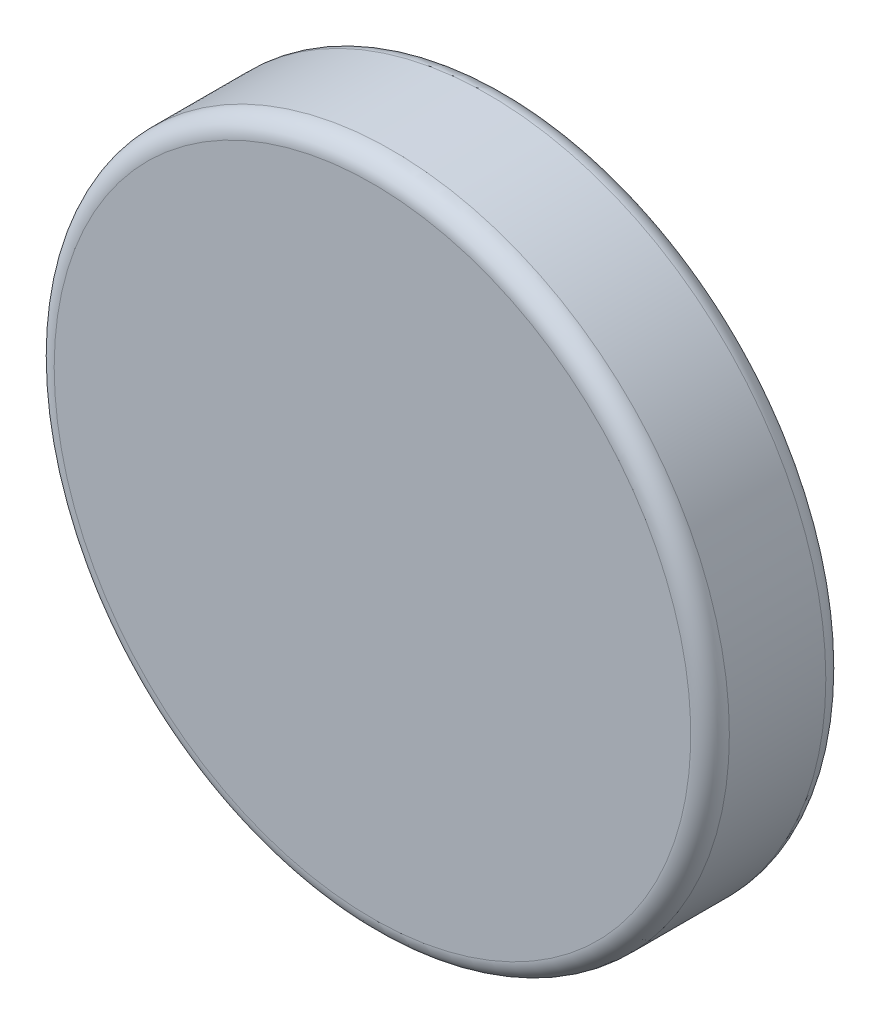
SolidWorks part; units mm, degrees
ref_plane "Front Plane" through (0, 0, 0) normal (0, 0, 1) x (1, 0, 0)
ref_plane "Top Plane" through (0, 0, 0) normal (0, 1, 0) x (1, 0, 0)
ref_plane "Right Plane" through (0, 0, 0) normal (1, 0, 0) x (0, 0, -1)
sketch "Sketch1" plane through (0, 0, 0) normal (0, 0, 1) x (1, 0, 0)
  circle A0 centre (-133.2708, 0) radius 4
  dimension "D1" = 8
extrude "Boss-Extrude1" add sketch "Sketch1" along normal blind 1
sketch "Sketch2" plane through (0, 0, 1) normal (0, 0, 1) x (1, 0, 0)
  arc A0 (-125.3812, 3.7838) -> (-125.3812, -3.7838) centre (-133.2708, 0) cw
  arc A2 (-125.3812, 3.7838) -> (-125.3812, -3.7838) centre (-133.2708, 0) ccw
  arc A3 (-125.3812, 3.7838) -> (-125.3812, -3.7838) centre (-133.2708, 0) ccw
  dimension "D1" = 0.5
extrude "Boss-Extrude2" add sketch "Sketch2" along normal offset from surface (3.5 mm away) 0.5
fillet "Fillet1" radius 0.5 2 edges at (-142.0208, 0, 1) (-129.2708, 0, 1)
sketch "Sketch3" plane through (0, 0, 4.5) normal (0, 0, 1) x (1, 0, 0)
  line L0 (-133.2708, 0) -> (-149.5, 0) construction
  arc A0 (-143.8767, 44.1558) -> (-143.8767, -44.1558) centre (0, 0) ccw construction
  circle A1 centre (-133.2708, 0) radius 16.2292
  point P4 (-150.5, 0)
  dimension "D1" = 1
extrude "Boss-Extrude3" [suppressed] add sketch "Sketch3" along normal blind 1
fillet "Fillet2" [suppressed] radius 0.5
fillet "Fillet3" radius 0.5 1 edges at (-142.0208, 0, 4.5)
equation "\"NubbinDiameter\" = 8"
equation "\"D1@Sketch1\"=\"NubbinDiameter\""
equation "\"FootToBedPlay\"=0.5"
equation "\"D1@Boss-Extrude2\"=\"FootToBedPlay\""
